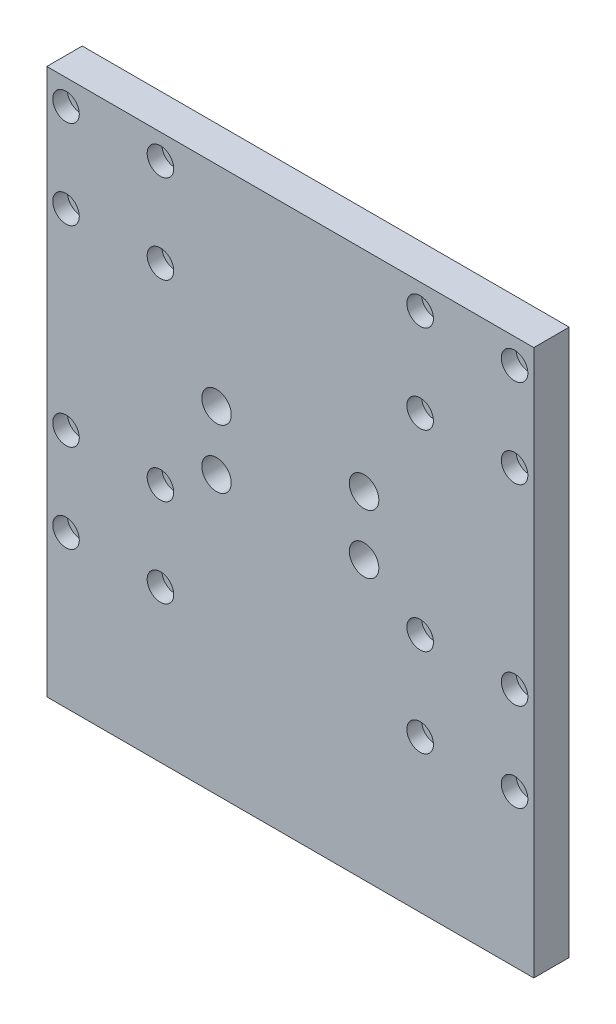
SolidWorks part; units mm, degrees
ref_plane "Plan de face" through (0, 0, 0) normal (0, 0, 1) x (1, 0, 0)
ref_plane "Plan de dessus" through (0, 0, 0) normal (0, 1, 0) x (1, 0, 0)
ref_plane "Plan de droite" through (0, 0, 0) normal (1, 0, 0) x (0, 0, -1)
sketch "Esquisse1" plane through (0, 0, 0) normal (0, 0, 1) x (1, 0, 0)
  line L1 (0, 0) -> (165, 0)
  line L2 (0, 0) -> (0, 140)
  line L3 (0, 140) -> (165, 140)
  line L4 (165, 0) -> (165, 140)
  dimension "D1" = 165
  dimension "D2" = 140
extrude "Boss.-Extru.1" add sketch "Esquisse1" along normal blind 12
sketch "Esquisse2" plane through (0, 0, 0) normal (0, 0, -1) x (-1, 0, 0)
  line L0 (-82.5, 0) -> (-82.5, 171.3338) construction
  line L1 (0, 0) -> (-165, 0) construction
  line L3 (-118.5, 103) -> (-46.5, 103)
  line L4 (-118.5, 103) -> (-118.5, 38)
  line L5 (-118.5, 38) -> (-46.5, 38)
  line L6 (-46.5, 103) -> (-46.5, 38)
  line L7 (-118.5, 103) -> (-46.5, 38) construction
  line L8 (-118.5, 38) -> (-46.5, 103) construction
  point P4 (-82.5, 70.5)
  dimension "D1" = 72
  dimension "D2" = 65
  dimension "D3" = 38
extrude "Enlèv. mat.-Extru.1" cut sketch "Esquisse2" against normal blind 4.5
sketch "Esquisse3" plane through (0, 0, 12) normal (0, 0, 1) x (1, 0, 0)
  line L0 (82.5, 140) -> (82.5, -3.3162) construction
  line L1 (165, 140) -> (0, 140) construction
  line L2 (165, 0) -> (165, 140) construction
  line L3 (0, 0) -> (165, 0) construction
  circle A0 centre (158.5, 6.5) radius 2.5
  circle A1 centre (158.5, 131.5) radius 2.5
  circle A2 centre (126.5, 6.5) radius 2.5
  circle A3 centre (126.5, 36.5) radius 2.5
  circle A4 centre (158.5, 36.5) radius 2.5
  circle A5 centre (126.5, 131.5) radius 2.5
  circle A6 centre (126.5, 101.5) radius 2.5
  circle A7 centre (158.5, 101.5) radius 2.5
  circle A8 centre (6.5, 6.5) radius 2.5
  circle A9 centre (6.5, 36.5) radius 2.5
  circle A10 centre (38.5, 6.5) radius 2.5
  circle A11 centre (38.5, 36.5) radius 2.5
  circle A12 centre (6.5, 101.5) radius 2.5
  circle A13 centre (38.5, 101.5) radius 2.5
  circle A14 centre (38.5, 131.5) radius 2.5
  circle A15 centre (6.5, 131.5) radius 2.5
  dimension "D1" = 5
  dimension "D2" = 6.5
  dimension "D3" = 95
  dimension "D4" = 5
  dimension "D5" = 6.5
  dimension "D6" = 6.5
  dimension "D7" = 2
  dimension "D8" = 2
  dimension "D9" = 2
  dimension "D10" = 2
extrude "Enlèv. mat.-Extru.2" cut sketch "Esquisse3" against normal up to next
sketch "Esquisse4" plane through (0, 0, 12) normal (0, 0, 1) x (1, 0, 0)
  line L0 (82.5, 140) -> (82.5, -5.1399) construction
  line L1 (165, 140) -> (0, 140) construction
  circle A0 centre (6.5, 131.5) radius 4.5
  circle A1 centre (6.5, 101.5) radius 4.5
  circle A2 centre (6.5, 36.5) radius 4.5
  circle A3 centre (6.5, 6.5) radius 4.5
  circle A4 centre (38.5, 6.5) radius 4.5
  circle A5 centre (38.5, 36.5) radius 4.5
  circle A6 centre (38.5, 101.5) radius 4.5
  circle A7 centre (38.5, 131.5) radius 4.5
  circle A8 centre (158.5, 101.5) radius 4.5
  circle A9 centre (158.5, 131.5) radius 4.5
  circle A10 centre (126.5, 131.5) radius 4.5
  circle A11 centre (126.5, 101.5) radius 4.5
  circle A12 centre (126.5, 6.5) radius 4.5
  circle A13 centre (158.5, 6.5) radius 4.5
  circle A14 centre (158.5, 36.5) radius 4.5
  circle A15 centre (126.5, 36.5) radius 4.5
  dimension "D1" = 9
  dimension "D2" = 9
  dimension "D3" = 9
  dimension "D4" = 9
  dimension "D5" = 9
  dimension "D6" = 9
  dimension "D7" = 9
  dimension "D8" = 9
extrude "Enlèv. mat.-Extru.3" cut sketch "Esquisse4" against normal blind 5
sketch "Esquisse5" plane through (0, 0, 0) normal (0, -1, 0) x (1, 0, 0)
  line L1 (0, 0) -> (165, 0)
  line L2 (0, 0) -> (0, 12)
  line L3 (0, 12) -> (165, 12)
  line L4 (165, 0) -> (165, 12)
extrude "Boss.-Extru.2" add sketch "Esquisse5" along normal blind 45
sketch "Esquisse6" plane through (0, 0, 4.5) normal (0, 0, -1) x (-1, 0, 0)
  line L0 (-82.5, 38) -> (-82.5, 83.2442) construction
  line L1 (-118.5, 38) -> (-46.5, 38) construction
  line L2 (-118.5, 38) -> (-46.5, 38) construction
  circle A0 centre (-57.5, 49) radius 5
  circle A1 centre (-57.5, 69) radius 5
  circle A2 centre (-107.5, 49) radius 5
  circle A3 centre (-107.5, 69) radius 5
  dimension "D1" = 11
  dimension "D2" = 20
  dimension "D3" = 10
  dimension "D4" = 10
  dimension "D5" = 25
extrude "Enlèv. mat.-Extru.4" cut sketch "Esquisse6" against normal up to next
